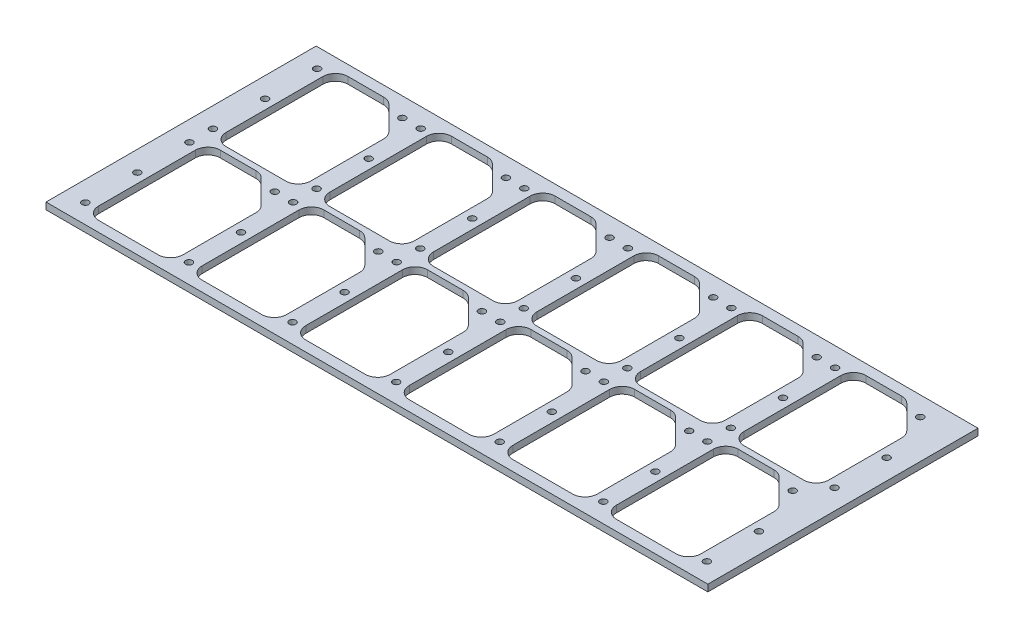
SolidWorks part; units mm, degrees
ref_plane "Front Plane" through (0, 0, 0) normal (0, 0, 1) x (1, 0, 0)
ref_plane "Top Plane" through (0, 0, 0) normal (0, 1, 0) x (1, 0, 0)
ref_plane "Right Plane" through (0, 0, 0) normal (1, 0, 0) x (0, 0, -1)
sketch "Sketch1" plane through (0, 0, 0) normal (0, 1, 0) x (1, 0, 0)
  line L1 (-311.15, -127) -> (311.15, -127)
  line L2 (-311.15, -127) -> (-311.15, 127)
  line L3 (-311.15, 127) -> (311.15, 127)
  line L4 (311.15, -127) -> (311.15, 127)
  line L5 (-311.15, -127) -> (311.15, 127) construction
  line L6 (-311.15, 127) -> (311.15, -127) construction
  point P0 (0, 0)
  dimension "D1" = 254
  dimension "D2" = 622.3
extrude "Boss-Extrude1" add sketch "Sketch1" along normal blind 6.35
sketch "Sketch2" plane through (0, 6.35, 0) normal (0, 1, 0) x (1, 0, 0)
  line L15 (-277.2, -14.5) -> (-277.2, -105.5) construction
  line L16 (-209.8, -105.5) -> (-209.8, -36.864) construction
  line L17 (-271.5, -111.2) -> (-215.5, -111.2) construction
  line L18 (-237.864, -8.8) -> (-271.5, -8.8) construction
  line L19 (-211.4695, -32.8335) -> (-233.8335, -10.4695) construction
  line L20 (-207.2269, -28.5908) -> (-229.5908, -6.2269)
  line L21 (-237.864, -2.8) -> (-271.5, -2.8)
  line L22 (-283.2, -14.5) -> (-283.2, -105.5)
  line L23 (-271.5, -117.2) -> (-215.5, -117.2)
  line L24 (-203.8, -105.5) -> (-203.8, -36.864)
  arc A15 (-233.8335, -10.4695) -> (-237.864, -8.8) centre (-237.864, -14.5) ccw construction
  arc A16 (-271.5, -8.8) -> (-277.2, -14.5) centre (-271.5, -14.5) ccw construction
  arc A17 (-209.8, -36.864) -> (-211.4695, -32.8335) centre (-215.5, -36.864) ccw construction
  arc A18 (-277.2, -105.5) -> (-271.5, -111.2) centre (-271.5, -105.5) ccw construction
  arc A19 (-215.5, -111.2) -> (-209.8, -105.5) centre (-215.5, -105.5) ccw construction
  arc A20 (-203.8, -36.864) -> (-207.2269, -28.5908) centre (-215.5, -36.864) ccw
  arc A21 (-229.5908, -6.2269) -> (-237.864, -2.8) centre (-237.864, -14.5) ccw
  arc A22 (-271.5, -2.8) -> (-283.2, -14.5) centre (-271.5, -14.5) ccw
  arc A23 (-283.2, -105.5) -> (-271.5, -117.2) centre (-271.5, -105.5) ccw
  arc A24 (-215.5, -117.2) -> (-203.8, -105.5) centre (-215.5, -105.5) ccw
  dimension "D6" = 6
  dimension "D7" = 6
  dimension "D8" = 6
  dimension "D9" = 6
  dimension "D10" = 6
  dimension "D1" = 6
  dimension "D2" = 6
  dimension "D3" = 6
  dimension "D4" = 6
  dimension "D5" = 6
extrude "Cut-Extrude1" cut sketch "Sketch2" against normal through all
pattern_linear "LPattern1" count 6 spacing 97.4 along (1, 0, 0) count 2 spacing 120 along (0, 0, -1) of "Cut-Extrude1"
sketch "Sketch3" plane through (0, 6.35, 0) normal (0, 1, 0) x (1, 0, 0)
  line L0 (-292.2, 60) -> (-292.2, 108.9551) construction
  line L1 (-292.2, 11.0449) -> (-292.2, 60) construction
  line L2 (-194.8, 11.0449) -> (-194.8, 60) construction
  line L3 (-194.8, 60) -> (-194.8, 108.9551) construction
  line L4 (-194.8, 108.9551) -> (-212.0449, 108.9551) construction
  line L5 (-243.5, 2.8) -> (-243.5, 60) construction
  line L6 (-271.5, 2.8) -> (-215.5, 2.8) construction
  line L7 (-243.5, 60) -> (-283.2, 60) construction
  line L8 (-283.2, 105.5) -> (-283.2, 14.5) construction
  line L9 (-292.2, 60) -> (-194.8, 60) construction
  line L10 (-218.4088, 102.5912) -> (-212.0449, 108.9551) construction
  line L11 (-207.2269, 91.4092) -> (-229.5908, 113.7731) construction
  line L12 (-203.8, 43.0325) -> (-185.8, 43.0325) construction
  line L13 (-203.8, 14.5) -> (-203.8, 83.136) construction
  line L14 (-185.8, 105.5) -> (-185.8, 14.5) construction
  line L15 (-194.8, 72.9185) -> (-203.8, 72.9185) construction
  circle A0 centre (-292.2, 108.9551) radius 3.175
  circle A1 centre (-292.2, 11.0449) radius 3.175
  circle A2 centre (-212.0449, 108.9551) radius 3.175
  circle A3 centre (-292.2, 60) radius 3.175
  circle A4 centre (-194.8, 60) radius 3.175
  circle A5 centre (-194.8, 11.0449) radius 3.175
  point P17 (-243.5, 60)
  point P30 (-194.8, 43.0325)
  dimension "D1" = 6.35
  dimension "D3" = 90
extrude "Cut-Extrude2" cut sketch "Sketch3" against normal through all
pattern_linear "LPattern2" count 6 spacing 97.4 along (1, 0, 0) count 2 spacing 120 along (0, 0, 1) of "Cut-Extrude2"
sketch "Sketch4" plane through (0, 6.35, 0) normal (0, 1, 0) x (1, 0, 0)
  point P0 (0, 0)
sketch "Sketch5" plane through (0, 0, 0) normal (0, -1, 0) x (1, 0, 0)
  point P0 (0, 0)
